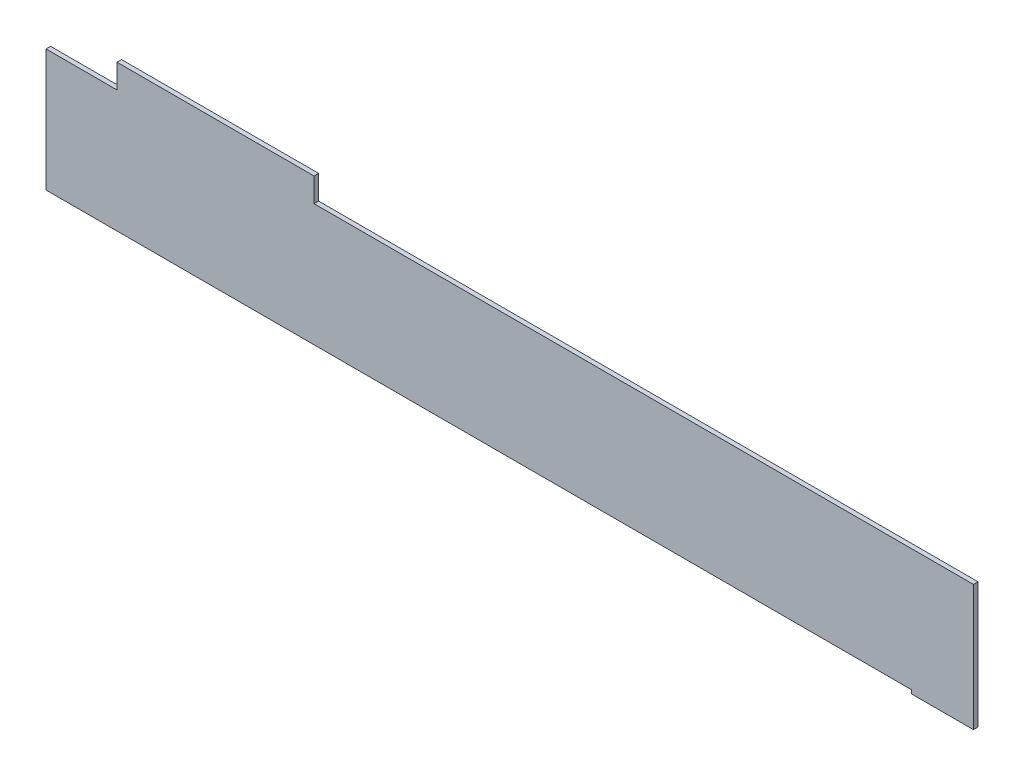
SolidWorks part; units mm, degrees
material "Custom Plastic"
ref_plane "X-Y Datum" through (0, 0, 0) normal (0, 0, 1) x (1, 0, 0)
ref_plane "X-Z Datum" through (0, 0, 0) normal (0, 1, 0) x (1, 0, 0)
ref_plane "Y-Z Datum" through (0, 0, 0) normal (1, 0, 0) x (0, 0, -1)
sketch "Sketch1" plane through (0, 0, 0) normal (0, 0, 1) x (1, 0, 0)
  line L1 (0, 0) -> (647.7, 0)
  line L2 (0, 0) -> (0, 85.344)
  line L3 (0, 85.344) -> (647.7, 85.344)
  line L4 (647.7, 0) -> (647.7, 85.344)
  line L5 (323.85, 85.344) -> (323.85, 0) construction
  line L6 (0, 42.672) -> (647.7, 42.672) construction
  point P296 (323.85, 42.672)
  dimension "D1" = 647.7
  dimension "D2" = 85.344
extrude "Boss-Extrude1" add sketch "Sketch1" against normal blind 3.175
sketch "Sketch2" plane through (0, 0, 0) normal (0, 0, 1) x (1, 0, 0)
  line L1 (647.7, 0) -> (604.52, 0)
  line L2 (647.7, 0) -> (647.7, -2.54)
  line L3 (647.7, -2.54) -> (604.52, -2.54)
  line L4 (604.52, 0) -> (604.52, -2.54)
  line L5 (626.11, -2.54) -> (626.11, 0) construction
  line L6 (647.7, -1.27) -> (604.52, -1.27) construction
  point P84 (626.11, -1.27)
  dimension "D1" = 43.18
  dimension "D2" = 2.54
extrude "Boss-Extrude2" add sketch "Sketch2" against normal up to surface (3.175 mm away) up to face at (323.85, 42.672, -3.175)
sketch "Sketch3" plane through (0, 0, 0) normal (0, 0, 1) x (1, 0, 0)
  line L0 (647.7, 85.344) -> (0, 85.344) construction
  line L1 (49.5554, 102.108) -> (187.2234, 102.108)
  line L2 (49.5554, 102.108) -> (49.5554, 85.344)
  line L3 (49.5554, 85.344) -> (187.2234, 85.344)
  line L4 (187.2234, 102.108) -> (187.2234, 85.344)
  line L5 (118.3894, 85.344) -> (118.3894, 102.108) construction
  line L6 (49.5554, 93.726) -> (187.2234, 93.726) construction
  line L7 (0, 85.344) -> (0, 0) construction
  point P60 (118.3894, 93.726)
  dimension "D1" = 49.5554
  dimension "D2" = 137.668
  dimension "D3" = 16.764
extrude "Boss-Extrude3" add sketch "Sketch3" against normal up to surface (3.175 mm away) up to face at (417.4067, 27.6013, -3.175)
